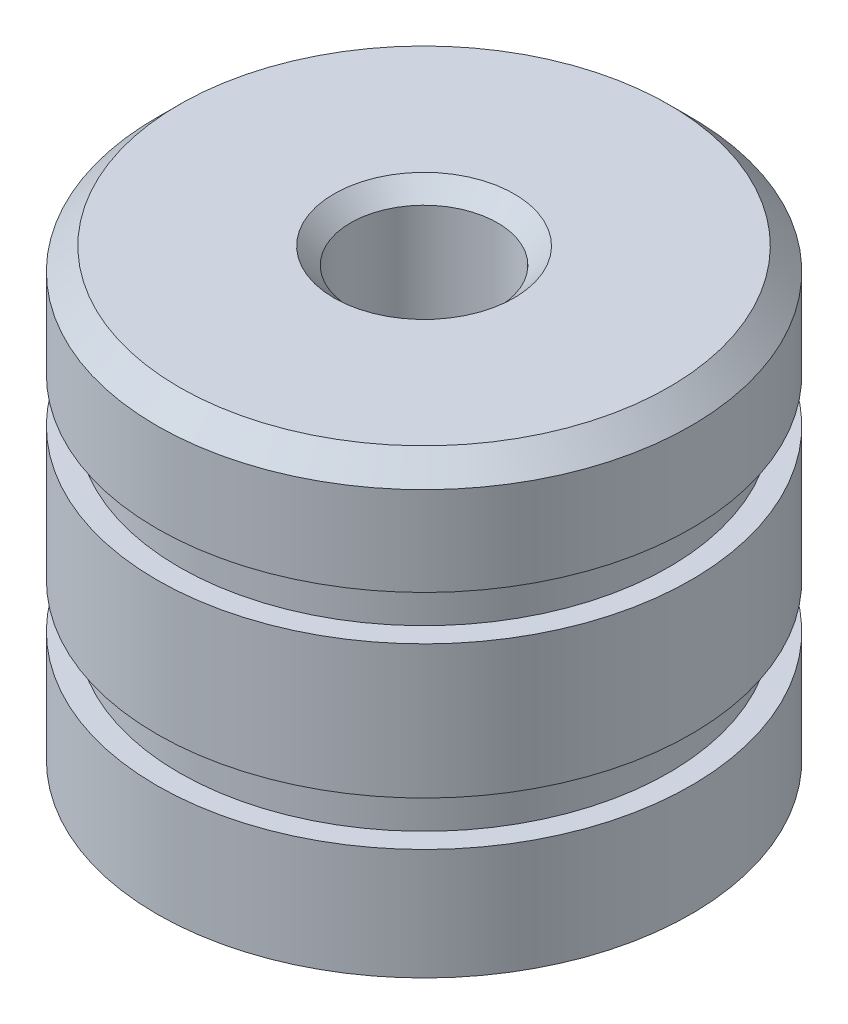
SolidWorks part; units mm, degrees
ref_plane "Front Plane" through (0, 0, 0) normal (0, 0, 1) x (1, 0, 0)
ref_plane "Top Plane" through (0, 0, 0) normal (0, 1, 0) x (1, 0, 0)
ref_plane "Right Plane" through (0, 0, 0) normal (1, 0, 0) x (0, 0, -1)
sketch "Sketch1" plane through (0, 0, 0) normal (0, 1, 0) x (1, 0, 0)
  circle A0 centre (0, 0) radius 6
  dimension "D1" = 12
extrude "Boss-Extrude1" add sketch "Sketch1" along normal mid plane 10
sketch "Sketch2" plane through (0, 5, 0) normal (0, 1, 0) x (1, 0, 0)
  circle A0 centre (0, 0) radius 5.5
  circle A1 centre (0, 0) radius 6 construction
  circle A2 centre (0, 0) radius 6
  dimension "D1" = 11
extrude "Cut-Extrude1" cut sketch "Sketch2" against normal blind 1 from offset 2.5 offset against normal yes
mirror "Mirror1" about plane through (0, 0, 0) normal (0, 1, 0) of "Cut-Extrude1"
chamfer "Chamfer1" distance 0.5 angle 45 1 edges at (0, 5, 6)
hole_wizard "M4x0.7 Tapped Hole1" positions "Sketch3" profile "Sketch4" tap size "M4x0.7" standard "ANSI Metric"
sketch "Sketch3" plane through (0, 5, 0) normal (0, 1, 0) x (1, 0, 0)
  point P0 (0, 0)
sketch "Sketch4" plane through (0, 5, 0) normal (1, 0, 0) x (0, 0, 1)
  line L0 (0, 0) -> (0, 8.9914)
  line L1 (0, 8.9914) -> (1.65, 8)
  line L2 (1.65, 8) -> (1.65, 0.375)
  line L3 (1.65, 0.375) -> (2.025, 0)
  line L5 (2.025, 0) -> (0, 0)
  line L6 (-1.65, 0.375) -> (-2.025, 0) construction
  line L10 (0, 8.9914) -> (-1.65, 8) construction
  line L11 (0, -6.35) -> (0, 107.95) construction
  dimension "Tap Drill Dia." = 3.3
  dimension "Tap Drill Depth" = 8
  dimension "Near C'Sink Dia." = 4.05
  dimension "Near C'Sink Angle" = 90
  dimension "Drill Angle" = 118
cosmetic thread "Hole Thread1" parameters "D1"=8, "D2"=4
